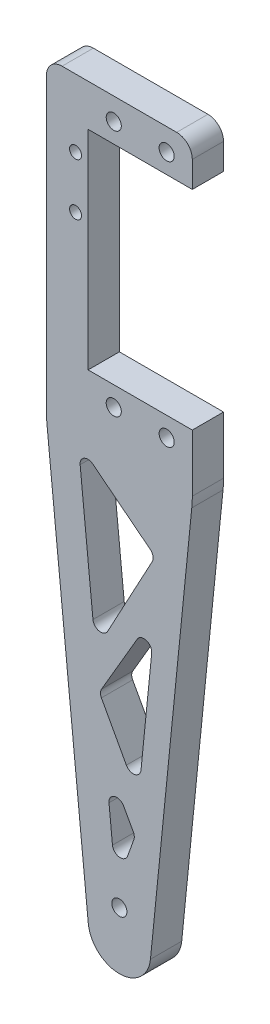
SolidWorks part; units mm, degrees
material "Acrylic (Medium-high impact)"
ref_plane "Front" through (0, 0, 0) normal (0, 0, 1) x (1, 0, 0)
ref_plane "Top" through (0, 0, 0) normal (0, 1, 0) x (1, 0, 0)
ref_plane "Right" through (0, 0, 0) normal (1, 0, 0) x (0, 0, -1)
sketch "Esquisse1" plane through (0, 0, 0) normal (0, 0, 1) x (1, 0, 0)
  line L0 (-14, -30) -> (-5.97, -110)
  line L1 (-14, 30) -> (14, 30)
  line L2 (-14, 30) -> (-14, -30)
  line L4 (14, 30) -> (14, 22)
  line L5 (14, -18) -> (14, -30)
  line L6 (14, 22) -> (-6, 22)
  line L8 (5.97, -110) -> (14, -30)
  line L10 (14, -18) -> (-6, -18)
  line L11 (-6, 22) -> (-6, -18)
  arc A0 (-5.97, -110) -> (5.97, -110) centre (0, -109.4008) ccw
  point P0 (0, 0)
  point P14 (-14, 0)
  point P21 (0, 30)
  dimension "D2" = 6
  dimension "D1" = 60
  dimension "D3" = 28
  dimension "D5" = 20
  dimension "D6" = 40
  dimension "D7" = 8
  dimension "D8" = 80
extrude "Boss.-Extru.1" add sketch "Esquisse1" along normal blind 6
fillet "Congé1" radius 3 2 edges at (-14, 30, 3) (14, 30, 3)
fillet "Congé2" radius 20 2 edges at (14, -30, 3) (-14, -30, 3)
sketch "Esquisse2" plane through (0, 0, 6) normal (0, 0, 1) x (1, 0, 0)
  line L0 (14, -18) -> (-6, -18) construction
  circle A1 centre (9.08, -21.75) radius 1.45
  circle A2 centre (-1.08, -21.75) radius 1.45
  circle A3 centre (-1.08, 25.75) radius 1.45
  circle A4 centre (9.08, 25.75) radius 1.45
  point P4 (4, -18)
  dimension "D1" = 5.08
  dimension "D2" = 3.75
  dimension "D3" = 2.9
  dimension "D5" = 2
  dimension "D4" = 2
extrude "Enlèv. mat.-Extru.1" cut sketch "Esquisse2" against normal up to next
sketch "Esquisse3" plane through (0, 0, 6) normal (0, 0, 1) x (1, 0, 0)
  line L6 (-7.8866, -31.0175) -> (-4.5844, -63.9162)
  line L7 (-4.5844, -63.9162) -> (6.8947, -42.6374)
  line L8 (6.8947, -42.6374) -> (-7.8866, -31.0175)
  line L15 (6.8947, -52.1218) -> (-3.8542, -70.5115)
  line L16 (-4.5844, -63.9162) -> (-2.7281, -80.6823) construction
  line L17 (-3.8542, -70.5115) -> (3.6639, -84.3099)
  line L18 (3.6639, -84.3099) -> (6.8947, -52.1218)
  line L19 (-2.7281, -80.6823) -> (-0.6632, -101.2543)
  line L20 (-0.6632, -101.2543) -> (3.0064, -91.0782)
  line L21 (3.0064, -91.0782) -> (-2.7281, -80.6823)
  line L23 (5.97, -110) -> (13.9, -30.9962) construction
  line L24 (-13.9, -30.9962) -> (-5.97, -110) construction
extrude "Enlèv. mat.-Extru.2" cut sketch "Esquisse3" against normal up to next
fillet "Congé3" radius 1.5 9 edges at (6.8947, -42.6374, 3) (-4.5844, -63.9162, 3) (-7.8866, -31.0175, 3) (3.0064, -91.0782, 3) (-2.7281, -80.6823, 3) (-0.6632, -101.2543, 3) (3.6639, -84.3099, 3) (-3.8542, -70.5115, 3) (6.8947, -52.1218, 3)
sketch "Esquisse4" plane through (0, 0, 6) normal (0, 0, 1) x (1, 0, 0)
  circle A0 centre (0, -104.4008) radius 1.45
  arc A1 (-5.97, -110) -> (5.97, -110) centre (0, -109.4008) ccw construction
  point P6 (0, -115.4008)
  dimension "D1" = 2.9
  dimension "D2" = 11
extrude "Enlèv. mat.-Extru.3" cut sketch "Esquisse4" against normal blind 6
sketch "Esquisse5" plane through (0, 0, 6) normal (0, 0, 1) x (1, 0, 0)
  line L0 (-6, 22) -> (14, 22) construction
  line L1 (-6, -18) -> (-6, 22) construction
  circle A0 centre (-8.41, 17) radius 1.15
  circle A1 centre (-8.41, 7) radius 1.15
  dimension "D1" = 2.3
  dimension "D2" = 5
  dimension "D3" = 2.41
  dimension "D4" = 2
extrude "Enlèv. mat.-Extru.4" cut sketch "Esquisse5" against normal blind 6
